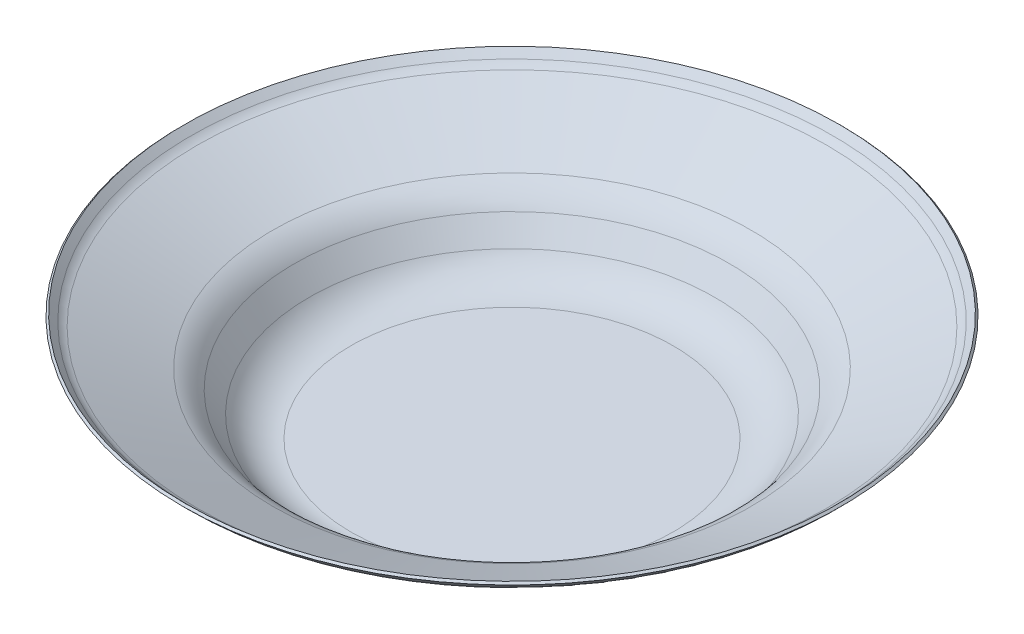
SolidWorks part; units mm, degrees
ref_plane "Front Plane" through (0, 0, 0) normal (0, 0, 1) x (1, 0, 0)
ref_plane "Top Plane" through (0, 0, 0) normal (0, 1, 0) x (1, 0, 0)
ref_plane "Right Plane" through (0, 0, 0) normal (1, 0, 0) x (0, 0, -1)
sketch "Sketch1" plane through (0, 0, 0) normal (0, 0, 1) x (1, 0, 0)
  line L0 (0, 0) -> (-30.3232, 0)
  line L1 (-38.4998, 4.243) -> (-41.3396, 8.2764)
  line L2 (-45.2017, 11.5408) -> (-59.3669, 18.3154)
  line L5 (-60.7451, 19.2905) -> (-61.9636, 20.5091)
  line L8 (0, 28.0498) -> (0, -5.3998) construction
  arc A0 (-41.3396, 8.2764) -> (-45.2017, 11.5408) centre (-49.5163, 2.5194) ccw
  arc A1 (-30.3232, 0) -> (-38.4998, 4.243) centre (-30.3232, 10) cw
  arc A2 (-59.3669, 18.3154) -> (-60.7451, 19.2905) centre (-57.2096, 22.8261) cw
  dimension "D1" = 10
  dimension "D2" = 10
  dimension "D3" = 5
revolve "Revolve-Thin2" add sketch "Sketch1" angle 360 about L8
